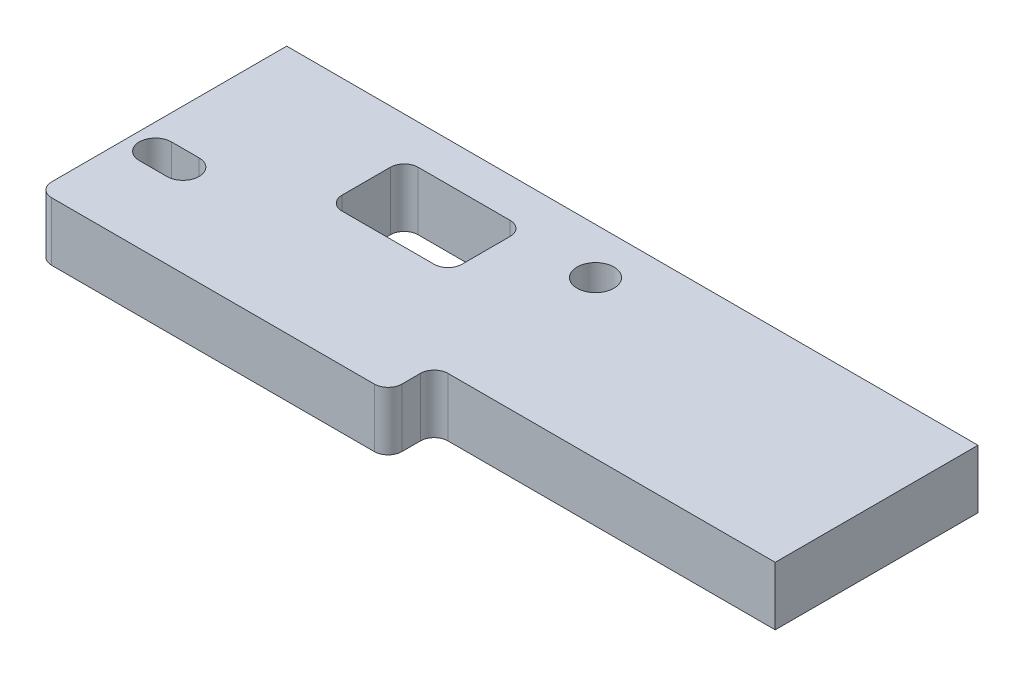
SolidWorks part; units mm, degrees
material "1060 Alloy"
ref_plane "Front Plane" through (0, 0, 0) normal (0, 0, 1) x (1, 0, 0)
ref_plane "Top Plane" through (0, 0, 0) normal (0, 1, 0) x (1, 0, 0)
ref_plane "Right Plane" through (0, 0, 0) normal (1, 0, 0) x (0, 0, -1)
sketch "Sketch1" plane through (0, 0, 0) normal (0, 1, 0) x (1, 0, 0)
  line L0 (38, 0) -> (38, 5)
  line L1 (0, 0) -> (38, 0)
  line L2 (0, 0) -> (0, 48.5)
  line L3 (7, 67.5) -> (34, 67.5)
  line L4 (96, 0) -> (96, 48.5)
  line L5 (0, 48.5) -> (7, 58.5)
  line L6 (7, 58.5) -> (7, 67.5)
  line L7 (34, 67.5) -> (34, 56.5)
  line L8 (48, -139.8616) -> (48, 139.8616) construction
  line L9 (58, 0) -> (58, 5)
  line L10 (96, 48.5) -> (89, 58.5)
  line L11 (89, 58.5) -> (89, 67.5)
  line L12 (62, 67.5) -> (62, 56.5)
  line L13 (38, 5) -> (58, 5)
  line L14 (58, 0) -> (96, 0)
  line L15 (34, 56.5) -> (62, 56.5)
  line L16 (62, 67.5) -> (89, 67.5)
  line L17 (79, 14.5) -> (66, 14.5)
  line L18 (17, 39) -> (30, 39)
  line L19 (17, 39) -> (17, 30.75)
  line L20 (17, 30.75) -> (30, 30.75)
  line L21 (30, 39) -> (30, 30.75)
  line L22 (17, 22.75) -> (30, 22.75)
  line L23 (17, 22.75) -> (17, 14.5)
  line L24 (17, 14.5) -> (30, 14.5)
  line L25 (30, 22.75) -> (30, 14.5)
  line L26 (66, 22.75) -> (66, 14.5)
  line L27 (79, 22.75) -> (66, 22.75)
  line L28 (79, 22.75) -> (79, 14.5)
  line L29 (79, 30.75) -> (66, 30.75)
  line L30 (66, 39) -> (66, 30.75)
  line L31 (79, 39) -> (66, 39)
  line L32 (79, 39) -> (79, 30.75)
  line L33 (2.75, 11.75) -> (5.75, 11.75)
  line L34 (2.75, 8.25) -> (5.75, 8.25)
  line L35 (93.25, 8.25) -> (90.25, 8.25)
  line L36 (93.25, 11.75) -> (90.25, 11.75)
  line L37 (-107.8769, 28.625) -> (107.8769, 28.625) construction
  line L38 (93.25, 45.5) -> (90.25, 45.5)
  line L39 (93.25, 49) -> (90.25, 49)
  line L40 (2.75, 49) -> (5.75, 49)
  line L41 (2.75, 45.5) -> (5.75, 45.5)
  circle A0 centre (38.5, 40) radius 2
  circle A1 centre (38.5, 22) radius 2
  circle A2 centre (57.5, 22) radius 2
  circle A3 centre (57.5, 40) radius 2
  arc A4 (2.75, 11.75) -> (2.75, 8.25) centre (2.75, 10) ccw
  arc A5 (5.75, 8.25) -> (5.75, 11.75) centre (5.75, 10) ccw
  arc A6 (93.25, 11.75) -> (93.25, 8.25) centre (93.25, 10) cw
  arc A7 (90.25, 8.25) -> (90.25, 11.75) centre (90.25, 10) cw
  arc A8 (93.25, 45.5) -> (93.25, 49) centre (93.25, 47.25) ccw
  arc A9 (90.25, 49) -> (90.25, 45.5) centre (90.25, 47.25) ccw
  arc A10 (2.75, 45.5) -> (2.75, 49) centre (2.75, 47.25) cw
  arc A11 (5.75, 49) -> (5.75, 45.5) centre (5.75, 47.25) cw
  circle A12 centre (12.5, 61.75) radius 3
  circle A13 centre (28, 61.75) radius 3
  circle A14 centre (68, 61.75) radius 3
  circle A15 centre (83.5, 61.75) radius 3
  point P14 (48, 0)
  point P59 (0, 28.625)
  dimension "D18" = 4
  dimension "D22" = 3.5
  dimension "D23" = 10
  dimension "D24" = 2.75
  dimension "D25" = 3.5
  dimension "D28" = 6
  dimension "D29" = 5.75
  dimension "D31" = 15.5
  dimension "D1" = 96
  dimension "D2" = 27
  dimension "D3" = 38
  dimension "D4" = 5
  dimension "D5" = 19
  dimension "D6" = 7
  dimension "D7" = 10
  dimension "D8" = 11
  dimension "D9" = 67.5
  dimension "D10" = 8.25
  dimension "D11" = 8.25
  dimension "D12" = 13
  dimension "D13" = 13
  dimension "D14" = 17
  dimension "D15" = 17
  dimension "D16" = 14.5
  dimension "D17" = 8
  dimension "D19" = 16.5
  dimension "D20" = 8.5
  dimension "D21" = 18
  dimension "D26" = 3
  dimension "D27" = 18.625
  dimension "D30" = 5.5
extrude "Boss-Extrude1" add sketch "Sketch1" along normal blind 6.35
fillet "Fillet1" radius 1.5 32 edges at (17, 3.175, -30.75) (17, 3.175, -14.5) (17, 3.175, -22.75) (17, 3.175, -39) (66, 3.175, -22.75) (66, 3.175, -39) (66, 3.175, -30.75) (66, 3.175, -14.5) (79, 3.175, -14.5) (79, 3.175, -30.75) (79, 3.175, -39) (79, 3.175, -22.75) (30, 3.175, -22.75) (30, 3.175, -14.5) (30, 3.175, -30.75) (30, 3.175, -39) (38, 3.175, -5) (58, 3.175, -5) (96, 3.175, -48.5) (89, 3.175, -58.5) (89, 3.175, -67.5) (62, 3.175, -67.5) (62, 3.175, -56.5) (34, 3.175, -56.5) (34, 3.175, -67.5) (7, 3.175, -67.5) (7, 3.175, -58.5) (0, 3.175, -48.5) (0, 3.175, 0) (96, 3.175, 0) (58, 3.175, 0) (38, 3.175, 0)
ref_plane "Plane1" through (48, 0, 0) normal (1, 0, 0) x (0, 0, -1)
sketch "Sketch2" plane through (48, 0, 0) normal (1, 0, 0) x (0, 0, -1)
  line L1 (-7.8701, 8.545) -> (74.4577, 8.545)
  line L2 (-7.8701, 8.545) -> (-7.8701, -5.9133)
  line L3 (-7.8701, -5.9133) -> (74.4577, -5.9133)
  line L4 (74.4577, 8.545) -> (74.4577, -5.9133)
extrude "Cut-Extrude1" cut sketch "Sketch2" along normal blind 51
sketch "Sketch3" plane through (48, 0, 0) normal (1, 0, 0) x (0, 0, -1)
  line L4 (5, 6.35) -> (5, 0)
  line L5 (5, 0) -> (56.5, 0)
  line L6 (56.5, 0) -> (56.5, 6.35)
  line L7 (56.5, 6.35) -> (5, 6.35)
  line L8 (5, 6.35) -> (5, 0)
  line L9 (5, 0) -> (56.5, 0)
  line L10 (56.5, 0) -> (56.5, 6.35)
  line L11 (56.5, 6.35) -> (5, 6.35)
  dimension "D1" = 0
extrude "Boss-Extrude2" add sketch "Sketch3" along normal blind 25
mirror "Mirror1" about plane through (73, 0, 0) normal (1, 0, 0) of bodies 103
ref_plane "Plane2" through (75, 0, 0) normal (1, 0, 0) x (0, 0, -1)
sketch "Sketch4" plane through (75, 0, 0) normal (1, 0, 0) x (0, 0, -1)
  line L1 (-8.4347, 14.082) -> (76.4943, 14.082)
  line L2 (-8.4347, 14.082) -> (-8.4347, -11.8039)
  line L3 (-8.4347, -11.8039) -> (76.4943, -11.8039)
  line L4 (76.4943, 14.082) -> (76.4943, -11.8039)
extrude "Cut-Extrude2" cut sketch "Sketch4" along normal blind 90
sketch "Sketch5" plane through (75, 0, 0) normal (1, 0, 0) x (0, 0, -1)
  line L0 (27, 6.35) -> (27, 0)
  line L1 (56.5, 6.35) -> (5, 6.35) construction
  line L2 (56.5, 0) -> (5, 0) construction
  line L3 (5, 6.35) -> (5, 0) construction
  line L4 (27, 6.35) -> (27.1, 6.35)
  line L5 (27.1, 6.35) -> (27.1, 0)
  line L6 (27.1, 0) -> (27, 0)
  dimension "D1" = 22
  dimension "D2" = 0.1
extrude "Cut-Extrude3" cut sketch "Sketch5" against normal blind 90
sketch "Sketch6" plane through (0, 0, -27) normal (0, 0, -1) x (-1, 0, 0)
  line L1 (-76.5488, 12.2353) -> (4.6965, 12.2353)
  line L2 (-76.5488, 12.2353) -> (-76.5488, -8.7778)
  line L3 (-76.5488, -8.7778) -> (4.6965, -8.7778)
  line L4 (4.6965, 12.2353) -> (4.6965, -8.7778)
extrude "Cut-Extrude4" cut sketch "Sketch6" along normal blind 71
